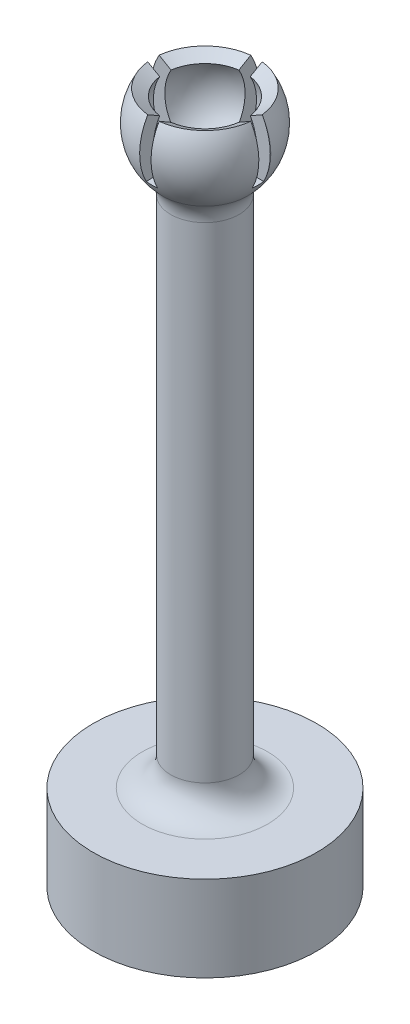
SolidWorks part; units mm, degrees
ref_plane "Front" through (0, 0, 0) normal (0, 0, 1) x (1, 0, 0)
ref_plane "Top" through (0, 0, 0) normal (0, 1, 0) x (1, 0, 0)
ref_plane "Right" through (0, 0, 0) normal (1, 0, 0) x (0, 0, -1)
sketch "Sketch1" plane through (0, 0, 0) normal (0, 0, 1) x (1, 0, 0)
  line L0 (0, 0) -> (0, 50)
  line L1 (0, 50) -> (9.8, 50)
  line L2 (9.8, 50) -> (9.8, 0)
  line L3 (9.8, 0) -> (0, 0)
  line L4 (0, 58) -> (0, 50) construction
  line L5 (3.5074, 60.025) -> (4.5466, 60.625)
  line L6 (0, 58) -> (5.25, 58) construction
  line L7 (3, 50) -> (3, 53.6916)
  line L8 (0, 58) -> (3.5074, 60.025) construction
  line L9 (9.8, 7.5) -> (3, 7.5)
  line L10 (3, 7.5) -> (3, 50)
  line L12 (0, 53.95) -> (0, 50)
  arc A0 (0, 53.95) -> (3.5074, 60.025) centre (0, 58) ccw
  arc A1 (3, 53.6916) -> (4.5466, 60.625) centre (0, 58) ccw
  dimension "D3" = 8.1
  dimension "D4" = 1.2
  dimension "D1" = 9.8
  dimension "D2" = 50
  dimension "D5" = 30
  dimension "D6" = 3
  dimension "D7" = 8
  dimension "D8" = 7.5
revolve "Revolve1" add sketch "Sketch1" angle 360 about L4
fillet "Fillet1" radius 2.5 2 edges at (-3, 53.6916, 0) (-3, 7.5, 0)
ref_plane "Plane1" through (0, 60.625, 0) normal (0, 1, 0) x (1, 0, 0)
sketch "Sketch3" plane through (0, 60.625, 0) normal (0, 1, 0) x (1, 0, 0)
  line L0 (0, 0) -> (0, -9.8) construction
  line L1 (-0.5, 0) -> (-0.5, -9.8)
  line L2 (0.5, 0) -> (0.5, -9.8)
  line L3 (0.5, -9.8) -> (-0.5, -9.8)
  line L4 (0, -0.5) -> (-9.8, -0.5)
  line L5 (0, 0.5) -> (-9.8, 0.5)
  line L6 (-9.8, -0.5) -> (-9.8, 0.5)
  line L7 (-0.5, 0) -> (-0.5, 9.8)
  line L8 (0.5, 0) -> (0.5, 9.8)
  line L9 (-0.5, 9.8) -> (0.5, 9.8)
  line L10 (0, 0.5) -> (9.8, 0.5)
  line L11 (0, -0.5) -> (9.8, -0.5)
  line L12 (9.8, 0.5) -> (9.8, -0.5)
  circle A0 centre (0, 0) radius 9.8 construction
  point P25 (0, 0)
  dimension "D1" = 0.5
  dimension "D2" = 0.5
  dimension "D3" = 4
extrude "Cut-Extrude1" cut sketch "Sketch3" against normal blind 5 contours L12 L10 L8 L2 L11 | L5 L10 L8 L9 L7 | L1 L7 L5 L6 L4 | L11 L0 L3 L2 | L0 L4 L1 L3
scale "Scale1" scale about origin uniform scaling yes scale factor 1.3
